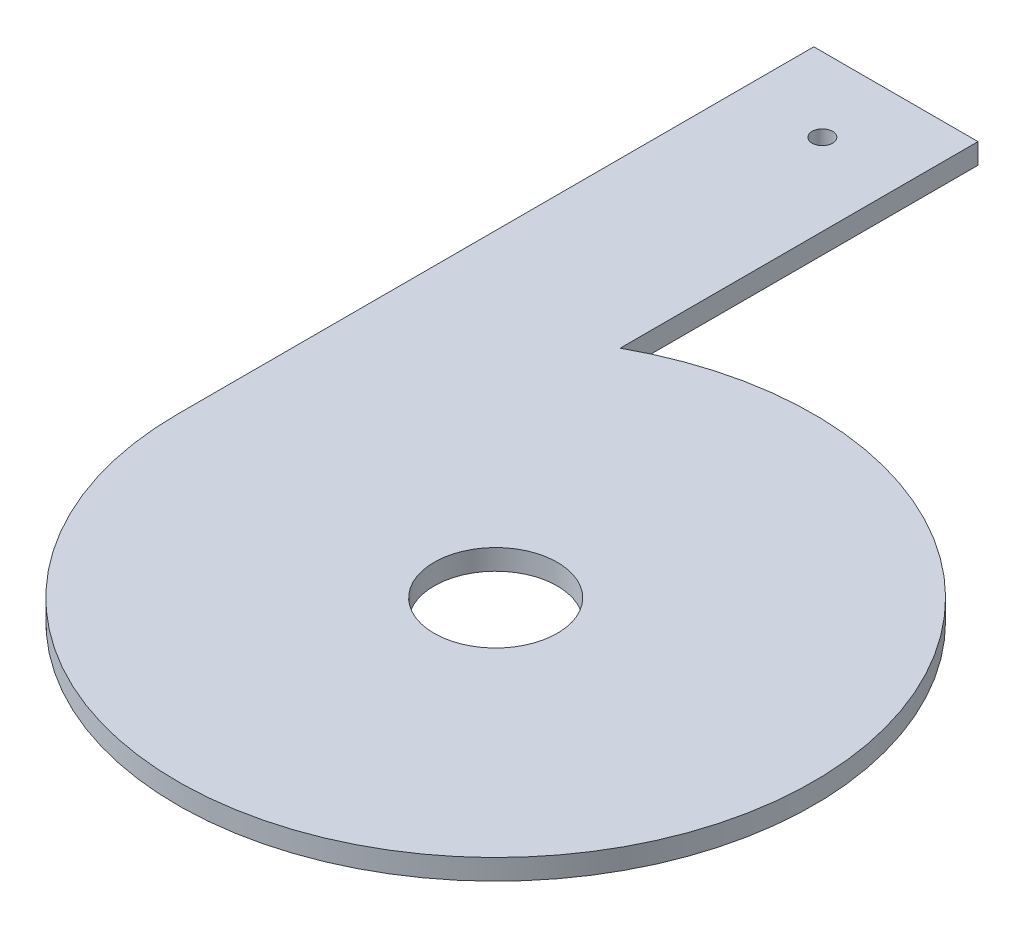
SolidWorks part; units mm, degrees
ref_plane "Front Plane" through (0, 0, 0) normal (0, 0, 1) x (1, 0, 0)
ref_plane "Top Plane" through (0, 0, 0) normal (0, 1, 0) x (1, 0, 0)
ref_plane "Right Plane" through (0, 0, 0) normal (1, 0, 0) x (0, 0, -1)
sketch "Sketch1" plane through (0, 0, 0) normal (0, 1, 0) x (1, 0, 0)
  circle A0 centre (0, 0) radius 31
extrude "Boss-Extrude1" add sketch "Sketch1" along normal blind 2
sketch "Sketch2" plane through (0, 2, 0) normal (0, 1, 0) x (1, 0, 0)
  circle A0 centre (0, 0) radius 6
extrude "Cut-Extrude1" cut sketch "Sketch2" against normal blind 2
sketch "Sketch3" plane through (0, 2, 0) normal (0, 1, 0) x (1, 0, 0)
  line L1 (-31, 0) -> (-15, 0)
  line L2 (-31, 0) -> (-31, 62)
  line L3 (-31, 62) -> (-15, 62)
  line L4 (-15, 0) -> (-15, 62)
  circle A0 centre (0, 0) radius 31 construction
  dimension "D1" = 62
  dimension "D2" = 16
extrude "Boss-Extrude2" add sketch "Sketch3" against normal blind 2
sketch "Sketch4" plane through (0, 2, 0) normal (0, 1, 0) x (1, 0, 0)
  line L3 (-15, 27.1293) -> (-15, 62)
  line L4 (-15, 62) -> (-31, 62)
  line L5 (-31, 62) -> (-31, 0)
  line L6 (-15, 27.1293) -> (-15, 62)
  line L7 (-15, 62) -> (-31, 62)
  line L8 (-31, 62) -> (-31, 0)
  line L10 (-20, 48.33) -> (-20, 61.23)
  line L11 (-25.9, 48.33) -> (-20, 48.33)
  line L12 (-25.9, 61.23) -> (-25.9, 48.33)
  line L13 (-20, 61.23) -> (-25.9, 61.23)
  line L14 (-20, 48.33) -> (-20, 61.23)
  line L15 (-25.9, 48.33) -> (-20, 48.33)
  line L16 (-25.9, 61.23) -> (-25.9, 48.33)
  line L17 (-20, 61.23) -> (-25.9, 61.23)
  arc A1 (-31, 0) -> (-15, 27.1293) centre (0, 0) ccw
  arc A2 (-31, 0) -> (-15, 27.1293) centre (0, 0) ccw
  dimension "D1" = 0
  dimension "D2" = 0
sketch "Sketch8" plane through (0, 0, 0) normal (0, -1, 0) x (1, 0, 0)
  circle A0 centre (-22.95, -54.78) radius 1 construction
  circle A1 centre (-22.95, -54.78) radius 1
sketch "Sketch10" plane through (0, 2, 0) normal (0, 1, 0) x (1, 0, 0)
  line L4 (-20, 48.33) -> (-20, 61.23)
  line L5 (-25.9, 48.33) -> (-20, 48.33)
  line L6 (-25.9, 61.23) -> (-25.9, 48.33)
  line L7 (-20, 61.23) -> (-25.9, 61.23)
  line L8 (-20, 48.33) -> (-20, 61.23)
  line L9 (-25.9, 48.33) -> (-20, 48.33)
  line L10 (-25.9, 61.23) -> (-25.9, 48.33)
  line L11 (-20, 61.23) -> (-25.9, 61.23)
  dimension "D1" = 0
sketch "Sketch11" plane through (0, 2, 0) normal (0, 1, 0) x (1, 0, 0)
  line L3 (-20, 61.23) -> (-25.9, 61.23) construction
  circle A0 centre (-22.95, 54.78) radius 1
  dimension "D1" = 6.45
extrude "Cut-Extrude2" cut sketch "Sketch11" against normal up to next
